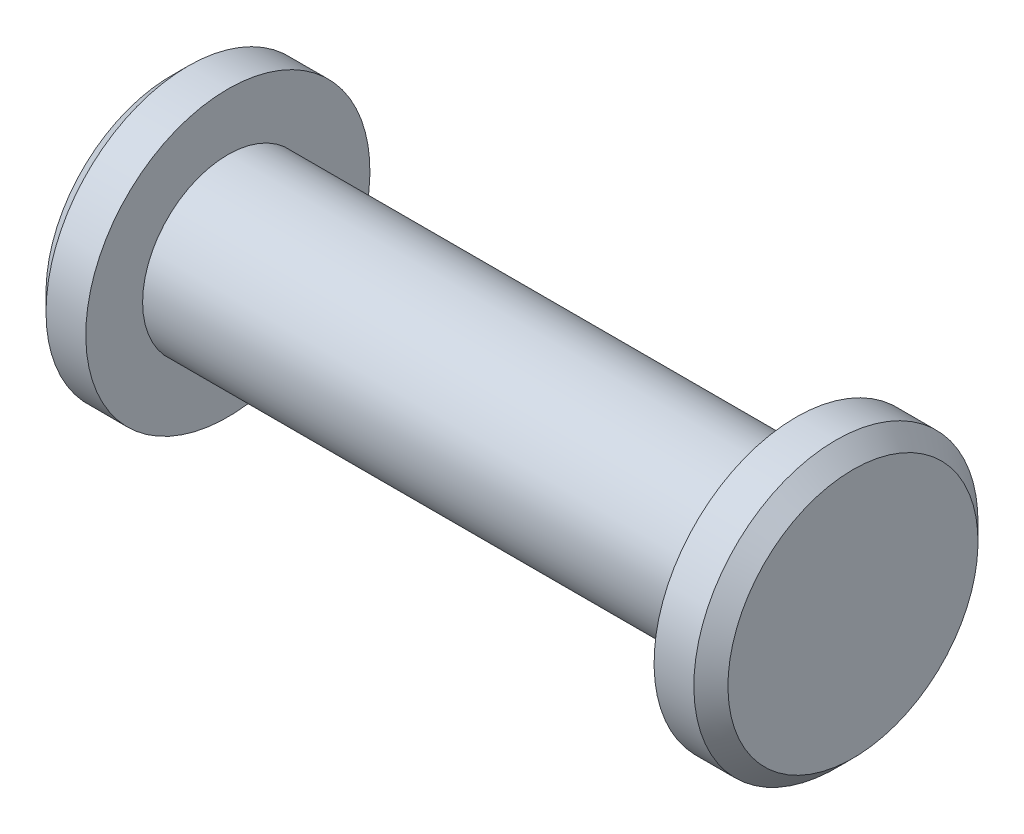
SolidWorks part; units mm, degrees
ref_plane "Front Plane" through (0, 0, 0) normal (0, 0, 1) x (1, 0, 0)
ref_plane "Top Plane" through (0, 0, 0) normal (0, 1, 0) x (1, 0, 0)
ref_plane "Right Plane" through (0, 0, 0) normal (1, 0, 0) x (0, 0, -1)
sketch "Sketch1" plane through (0, 0, 0) normal (0, 0, 1) x (1, 0, 0)
  line L0 (-120, 0) -> (-120, 25)
  line L1 (-120, 25) -> (-110, 25)
  line L2 (-110, 25) -> (-110, 15)
  line L3 (-110, 15) -> (-10, 15)
  line L4 (-10, 15) -> (-10, 25)
  line L5 (-10, 25) -> (0, 25)
  line L6 (0, 25) -> (0, 0)
  line L7 (0, 0) -> (-120, 0)
  dimension "D1" = 100
  dimension "D2" = 10
  dimension "D3" = 10
  dimension "D4" = 15
  dimension "D5" = 25
revolve "Revolve1" add sketch "Sketch1" angle 360 about L7
chamfer "Chamfer1" distance 3 angle 45 2 edges at (-120, 25, 0) (0, 25, 0)
